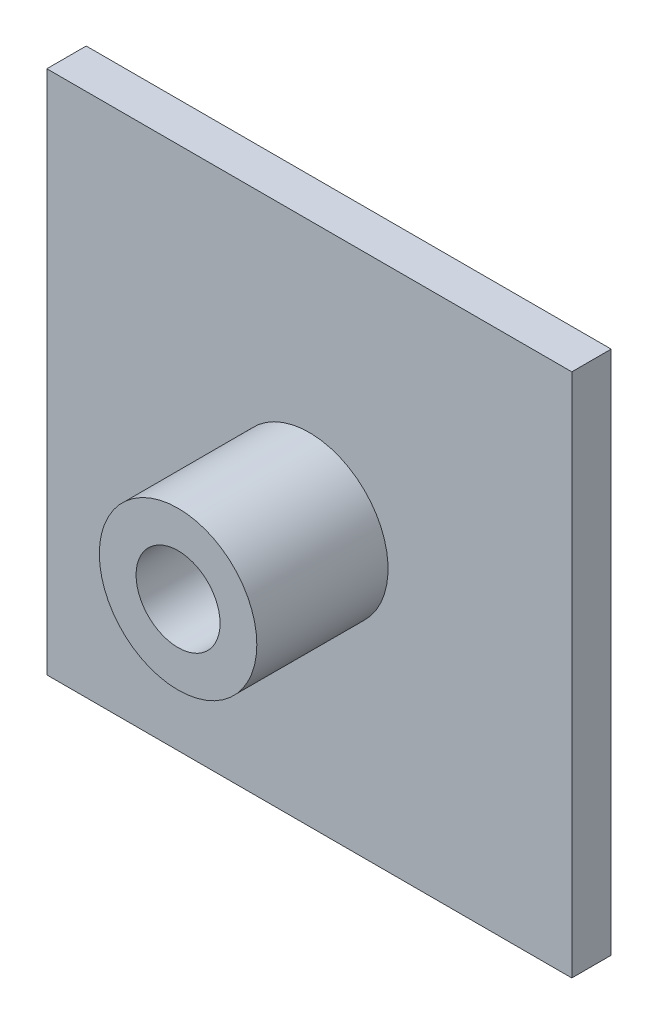
SolidWorks part; units mm, degrees
material "ABS"
ref_plane "Front" through (0, 0, 0) normal (0, 0, 1) x (1, 0, 0)
ref_plane "Top" through (0, 0, 0) normal (0, 1, 0) x (1, 0, 0)
ref_plane "Right" through (0, 0, 0) normal (1, 0, 0) x (0, 0, -1)
sketch "Эскиз2" plane through (0, 0, 0) normal (0, 0, 1) x (1, 0, 0)
  line L1 (-10, -10) -> (10, -10)
  line L2 (-10, -10) -> (-10, 10)
  line L3 (-10, 10) -> (10, 10)
  line L4 (10, -10) -> (10, 10)
  line L5 (-10, -10) -> (10, 10) construction
  line L6 (-10, 10) -> (10, -10) construction
  circle A0 centre (0, 0) radius 1.6
  point P0 (0, 0)
  dimension "D2" = 3.2
  dimension "D1" = 20
extrude "Основание" add sketch "Эскиз2" along normal blind 1.5
sketch "Эскиз3" plane through (0, 0, 1.5) normal (0, 0, 1) x (1, 0, 0)
  circle A0 centre (0, 0) radius 3
  circle A3 centre (0, 0) radius 1.6
  circle A4 centre (0, 0) radius 1.6 construction
  dimension "D1" = 6
  dimension "D2" = 1.4
extrude "Стойка" add sketch "Эскиз3" along normal blind 5
chamfer "Фаска1" distance 1.5 angle 45 1 edges at (1.6, 0, 0)
